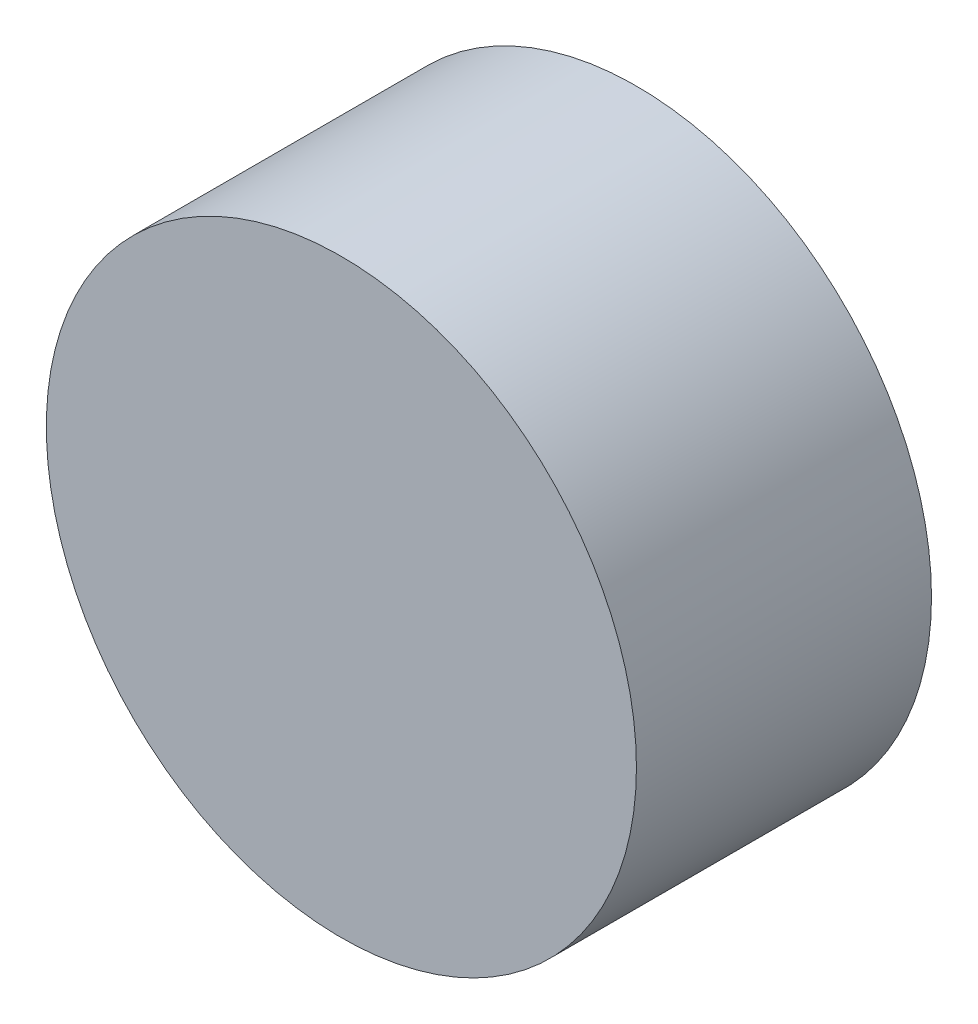
SolidWorks part; units mm, degrees
ref_plane "Front Plane" through (0, 0, 0) normal (0, 0, 1) x (1, 0, 0)
ref_plane "Top Plane" through (0, 0, 0) normal (0, 1, 0) x (1, 0, 0)
ref_plane "Right Plane" through (0, 0, 0) normal (1, 0, 0) x (0, 0, -1)
sketch "Sketch1" plane through (0, 0, 0) normal (0, 0, 1) x (1, 0, 0)
  circle A0 centre (0, 0) radius 5.08
extrude "Boss-Extrude1" add sketch "Sketch1" along normal blind 5.08
